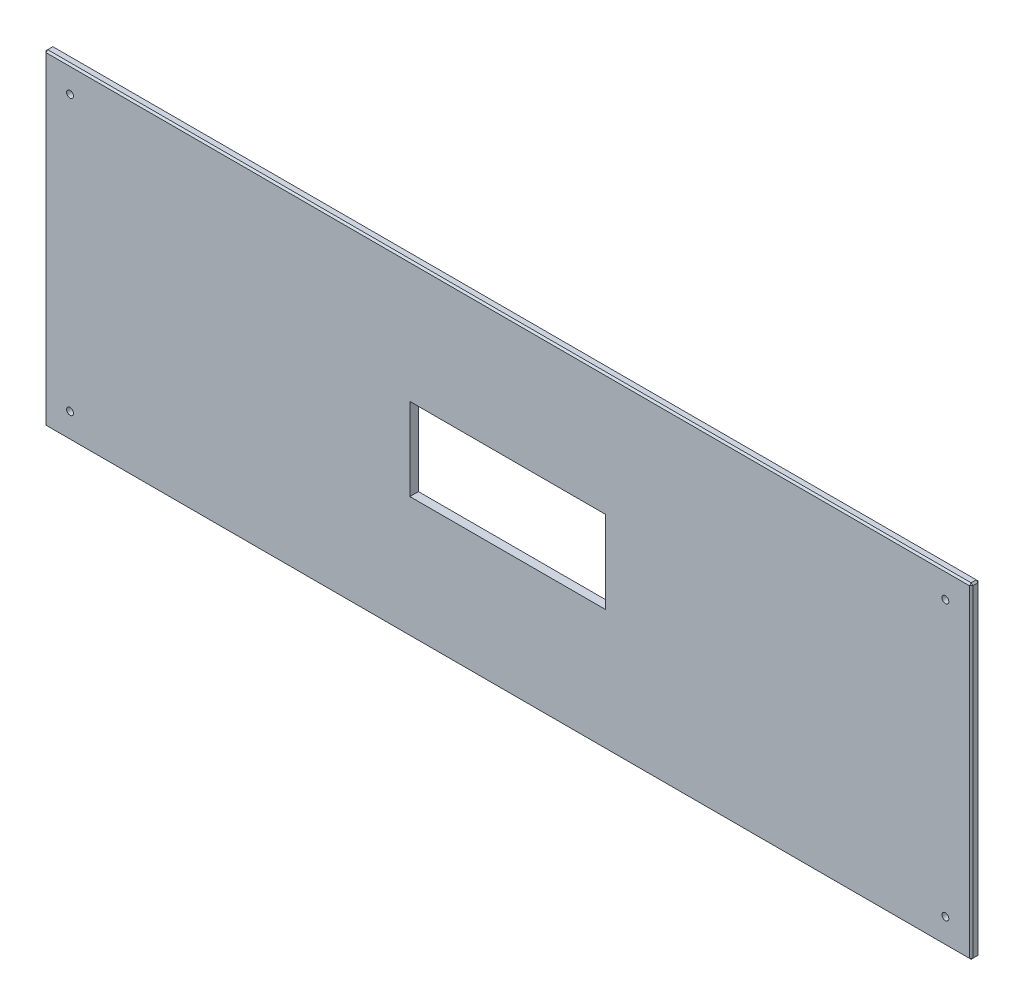
SolidWorks part; units mm, degrees
material "ABS"
ref_plane "Front Plane" through (0, 0, 0) normal (0, 0, 1) x (1, 0, 0)
ref_plane "Top Plane" through (0, 0, 0) normal (0, 1, 0) x (1, 0, 0)
ref_plane "Right Plane" through (0, 0, 0) normal (1, 0, 0) x (0, 0, -1)
sketch "Sketch1" plane through (0, 0, 0) normal (0, 0, 1) x (1, 0, 0)
  line L1 (0, 0) -> (540, 0)
  line L2 (0, 0) -> (0, 190)
  line L3 (0, 190) -> (540, 190)
  line L4 (540, 0) -> (540, 190)
  dimension "D1" = 540
  dimension "D2" = 190
extrude "Boss-Extrude1" add sketch "Sketch1" along normal blind 5
chamfer "Chamfer1" distance 1 angle 45 12 edges at (270, 0, 0) (540, 95, 0) (270, 190, 0) (0, 95, 0) (270, 190, 5) (0, 190, 2.5) (0, 95, 5) (0, 0, 2.5) (270, 0, 5) (540, 0, 2.5) (540, 95, 5) (540, 190, 2.5)
sketch "Sketch2" plane through (0, 0, 5) normal (0, 0, 1) x (1, 0, 0)
  line L0 (1, 190) -> (539, 190) construction
  line L1 (15, 175) -> (525, 175) construction
  line L2 (15, 175) -> (15, 15) construction
  line L3 (15, 15) -> (525, 15) construction
  line L4 (525, 175) -> (525, 15) construction
  line L5 (540, 189) -> (540, 1) construction
  line L6 (539, 0) -> (1, 0) construction
  line L7 (0, 1) -> (0, 189) construction
  circle A0 centre (525, 175) radius 2
  circle A1 centre (525, 15) radius 2
  circle A2 centre (15, 175) radius 2
  circle A3 centre (15, 15) radius 2
  dimension "D5" = 4
  dimension "D6" = 4
  dimension "D7" = 4
  dimension "D8" = 4
  dimension "D1" = 15
  dimension "D2" = 15
  dimension "D3" = 15
  dimension "D4" = 15
extrude "Cut-Extrude1" cut sketch "Sketch2" against normal blind 5
sketch "Sketch3" plane through (0, 0, 5) normal (0, 0, 1) x (1, 0, 0)
  line L0 (270, 189) -> (270, 1) construction
  line L1 (213, 119) -> (327, 119)
  line L2 (213, 119) -> (213, 71)
  line L3 (213, 71) -> (327, 71)
  line L4 (327, 119) -> (327, 71)
  line L5 (539, 189) -> (1, 189) construction
  line L6 (1, 1) -> (539, 1) construction
  line L7 (1, 95) -> (539, 95) construction
  line L8 (1, 189) -> (1, 1) construction
  line L9 (539, 1) -> (539, 189) construction
  dimension "D1" = 114
  dimension "D2" = 48
  dimension "D3" = 57
  dimension "D4" = 24
extrude "Cut-Extrude2" cut sketch "Sketch3" against normal blind 10
